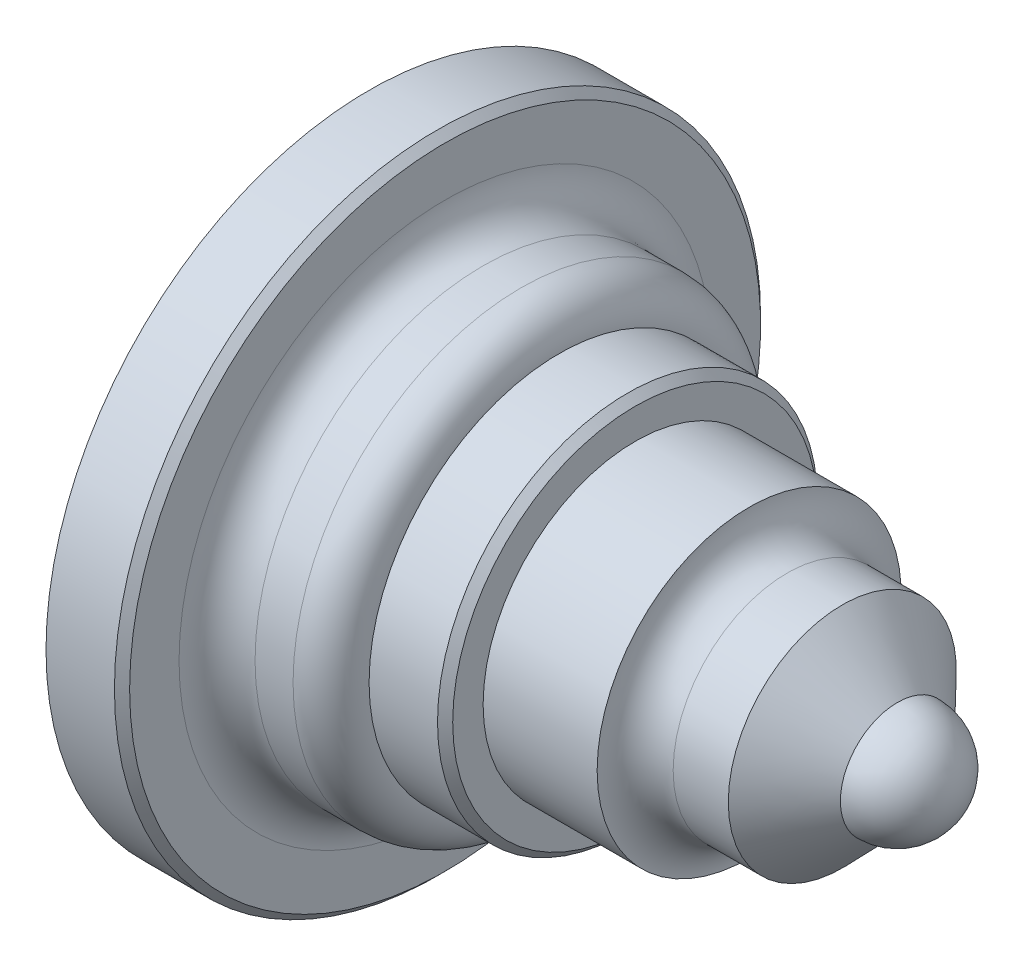
SolidWorks part; units mm, degrees
ref_plane "Front Plane" through (0, 0, 0) normal (0, 0, 1) x (1, 0, 0)
ref_plane "Top Plane" through (0, 0, 0) normal (0, 1, 0) x (1, 0, 0)
ref_plane "Right Plane" through (0, 0, 0) normal (1, 0, 0) x (0, 0, -1)
sketch "Sketch1" plane through (0, 0, 0) normal (0, 0, 1) x (1, 0, 0)
  line L0 (0, 0) -> (77, 0)
  line L1 (0, 0) -> (0, 42.5)
  line L7 (62.25, 15) -> (55, 15)
  line L10 (50, 20) -> (35, 20)
  line L11 (35, 20) -> (35, 24)
  line L14 (35, 24) -> (34, 25)
  line L15 (34, 25) -> (25, 25)
  line L16 (20, 30) -> (15, 30)
  line L19 (10, 35) -> (10, 41.5)
  line L22 (10, 41.5) -> (9, 42.5)
  line L23 (0, 42.5) -> (9, 42.5)
  line L24 (69.5, 7.5) -> (62.25, 15)
  arc A1 (77, 0) -> (69.5, 7.5) centre (69.5, 0) ccw
  arc A2 (50, 20) -> (55, 15) centre (55, 20) ccw
  arc A3 (25, 25) -> (20, 30) centre (20, 25) ccw
  arc A4 (10, 35) -> (15, 30) centre (15, 35) ccw
  dimension "D1" = 77
  dimension "D2" = 42.5
  dimension "D3" = 7.25
  dimension "D4" = 7.25
  dimension "D5" = 15
  dimension "D6" = 4
  dimension "D7" = 9
  dimension "D8" = 5
  dimension "D9" = 6.5
  dimension "D10" = 7.5
revolve "Revolve1" add sketch "Sketch1" angle 360 about L0
